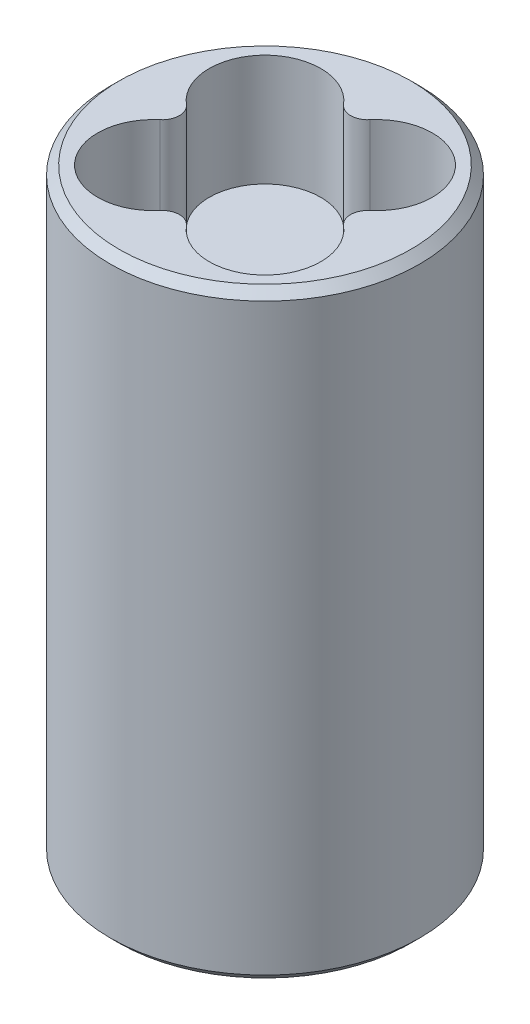
SolidWorks part; units mm, degrees
ref_plane "Front Plane" through (0, 0, 0) normal (0, 0, 1) x (1, 0, 0)
ref_plane "Top Plane" through (0, 0, 0) normal (0, 1, 0) x (1, 0, 0)
ref_plane "Right Plane" through (0, 0, 0) normal (1, 0, 0) x (0, 0, -1)
sketch "Sketch3" plane through (0, 0, 0) normal (0, 1, 0) x (1, 0, 0)
  circle A0 centre (0, 0) radius 9
  dimension "D1" = 18
extrude "Boss-Extrude3" add sketch "Sketch3" along normal blind 35
sketch "Sketch4" plane through (0, 35, 0) normal (0, 1, 0) x (1, 0, 0)
  line L5 (6.5, -6.5) -> (-6.5, -6.5)
  line L6 (6.5, -6.5) -> (6.5, 6.5)
  line L7 (6.5, 6.5) -> (-6.5, 6.5)
  line L8 (-6.5, -6.5) -> (-6.5, 6.5)
  line L9 (6.5, -6.5) -> (-6.5, 6.5) construction
  line L10 (6.5, 6.5) -> (-6.5, -6.5) construction
  circle A0 centre (-3.25, 3.25) radius 3.25
  circle A1 centre (-3.25, -3.25) radius 3.25
  circle A2 centre (3.25, 3.25) radius 3.25
  circle A3 centre (3.25, -3.25) radius 3.25
  point P0 (0, 0)
  point P11 (0, 0)
  dimension "D1" = 6.5
extrude "Cut-Extrude1" cut sketch "Sketch4" against normal blind 6.5 contours A0 | A1 | A3 | A2 | A3 A2 A0 A1
fillet "Fillet1" radius 1 4 edges at (-3.25, 31.75, 0) (0, 31.75, 3.25) (3.25, 31.75, 0) (0, 31.75, -3.25)
sketch "Sketch1" plane through (0, 0, 0) normal (0, -1, 0) x (-1, 0, 0)
  circle A1 centre (0, 0) radius 3.05
  dimension "D2" = 6.1
extrude "Cut-Extrude2" cut sketch "Sketch1" against normal blind 7
chamfer "Chamfer1" distance 3.05 angle 45 1 edges at (0, 7, -3.05)
chamfer "Chamfer2" distance 0.5 angle 45 2 edges at (0, 0, 9) (0, 35, 9)
